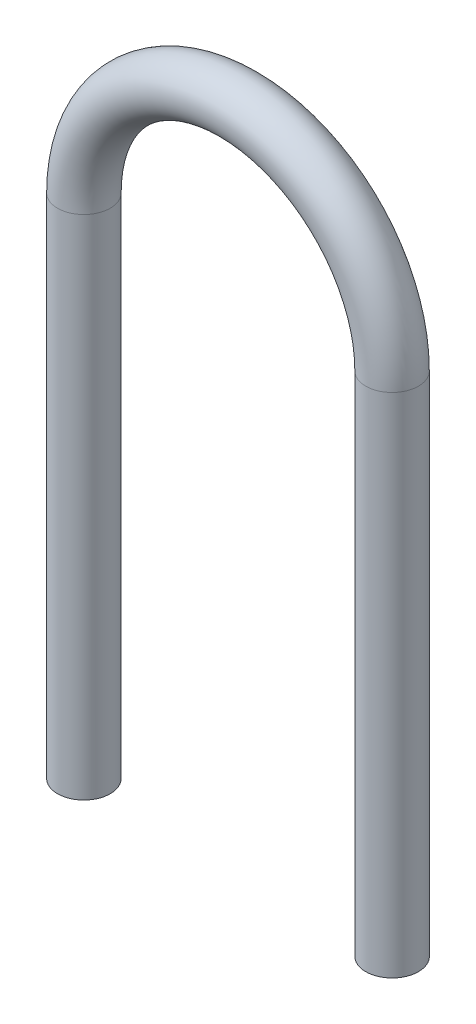
SolidWorks part; units mm, degrees
material "AISI 1045 Steel, cold drawn"
ref_plane "Front Plane" through (0, 0, 0) normal (0, 0, 1) x (1, 0, 0)
ref_plane "Top Plane" through (0, 0, 0) normal (0, 1, 0) x (1, 0, 0)
ref_plane "Right Plane" through (0, 0, 0) normal (1, 0, 0) x (0, 0, -1)
sketch "Sketch1" plane through (0, 0, 0) normal (0, 1, 0) x (1, 0, 0)
  circle A0 centre (0, 0) radius 0.508
  circle A1 centre (5.9436, 0) radius 0.508
  dimension "D1" = 1.016
  dimension "D2" = 1.016
  dimension "D3" = 5.9436
extrude "Boss-Extrude1" add sketch "Sketch1" along normal blind 9.779
sketch "Sketch2" plane through (0, 9.779, 0) normal (0, 1, 0) x (1, 0, 0)
  line L0 (0, 0) -> (0.508, 0)
  circle A0 centre (0, 0) radius 0.508 construction
ref_plane "Plane1" through (0, 0, 0) normal (0, 0, 1) x (1, 0, 0)
sketch "Sketch3" plane through (0, 0, 0) normal (0, 0, 1) x (1, 0, 0)
  line L0 (6.4516, 9.779) -> (5.4356, 9.779) construction
  arc A0 (0, 9.779) -> (5.9436, 9.779) centre (2.9718, 9.779) cw
sketch "Sketch4" plane through (0, 9.779, 0) normal (0, 1, 0) x (1, 0, 0)
  circle A0 centre (0, 0) radius 0.508
  dimension "D1" = 1.016
sweep "Sweep1" add profiles "Sketch4" path "Sketch3"
